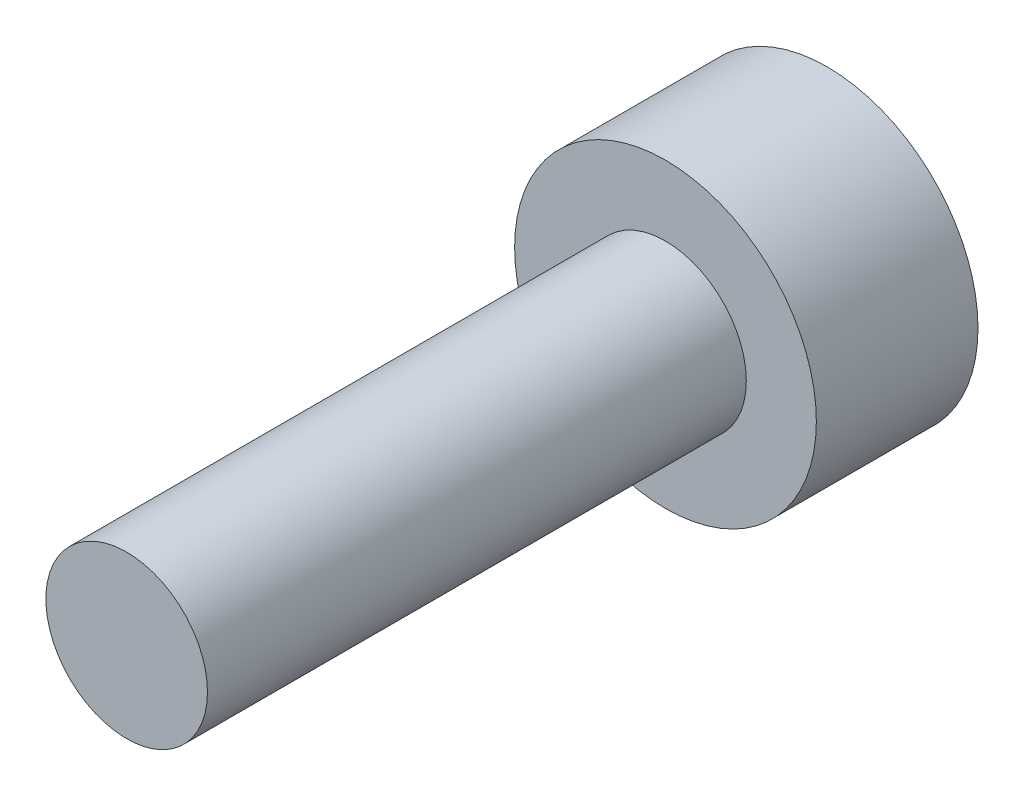
SolidWorks part; units mm, degrees
ref_plane "Front Plane" through (0, 0, 0) normal (0, 0, 1) x (1, 0, 0)
ref_plane "Top Plane" through (0, 0, 0) normal (0, 1, 0) x (1, 0, 0)
ref_plane "Right Plane" through (0, 0, 0) normal (1, 0, 0) x (0, 0, -1)
sketch "Sketch1" plane through (0, 0, 0) normal (0, 0, 1) x (1, 0, 0)
  circle A0 centre (0, 0) radius 2.8
extrude "Head" add sketch "Sketch1" along normal blind 3 from offset 3
sketch "Sketch2" plane through (0, 0, 0) normal (0, 0, 1) x (1, 0, 0)
  circle A0 centre (0, 0) radius 1.5
extrude "Shank" add sketch "Sketch2" along normal blind 10
sketch "Sketch3" plane through (0, 0, 0) normal (0, 0, 1) x (1, 0, 0)
  line L0 (1.25, 0.7217) -> (0, 1.4434)
  line L1 (0, 1.4434) -> (-1.25, 0.7217)
  line L2 (-1.25, 0.7217) -> (-1.25, -0.7217)
  line L3 (-1.25, -0.7217) -> (0, -1.4434)
  line L4 (0, -1.4434) -> (1.25, -0.7217)
  line L5 (1.25, -0.7217) -> (1.25, 0.7217)
extrude "Hex socket" cut sketch "Sketch3" along normal blind 1.8 from offset 3.2
